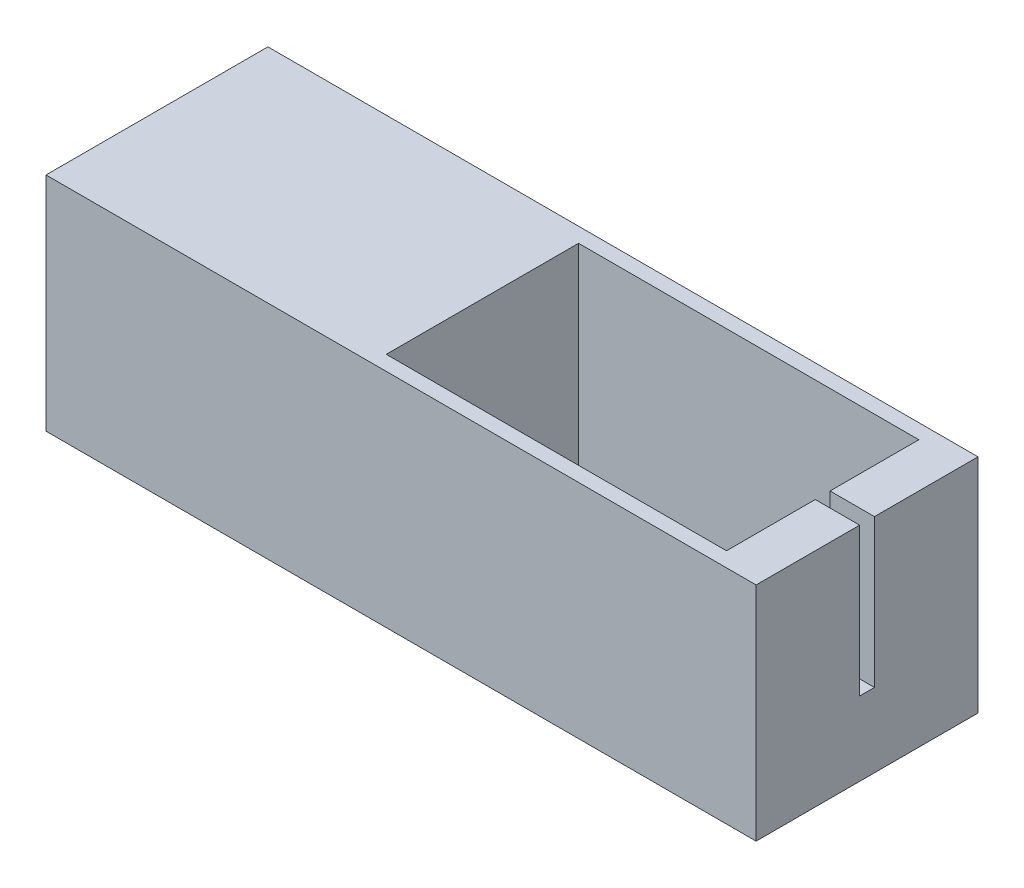
SolidWorks part; units mm, degrees
other "Markup1"
sketch "Sketch10" plane through (-5, 0, 7) normal (-0.8048, -0.3559, 0.4749) x (0.4785, -0.8625, 0.1645)
material "Very Low Density PE (SS)"
ref_plane "Front Plane" through (0, 0, 0) normal (0, 0, 1) x (1, 0, 0)
ref_plane "Top Plane" through (0, 0, 0) normal (0, 1, 0) x (1, 0, 0)
ref_plane "Right Plane" through (0, 0, 0) normal (1, 0, 0) x (0, 0, -1)
sketch "Sketch1" plane through (0, 0, 0) normal (0, 1, 0) x (1, 0, 0)
  circle A0 centre (0, 0) radius 3.5
  dimension "D1" = 7
extrude "Boss-Extrude1" add sketch "Sketch1" along normal blind 5
sketch "Sketch2" plane through (0, 0, 0) normal (0, -1, 0) x (1, 0, 0)
  circle A0 centre (0, 0) radius 2.5
  dimension "D1" = 5
extrude "Cut-Extrude1" cut sketch "Sketch2" against normal blind 4.5
sketch "Sketch3" plane through (0, 5, 0) normal (0, 1, 0) x (1, 0, 0)
  line L0 (0.3741, -3.4799) -> (14.7084, -1.9388)
  line L1 (14.7084, 1.9388) -> (0.3741, 3.4799)
  arc A0 (14.7084, -1.9388) -> (14.7084, 1.9388) centre (14.5, 0) ccw
  circle A1 centre (0, 0) radius 3.5 construction
  arc A2 (0.3741, -3.4799) -> (0.3741, 3.4799) centre (0, 0) ccw
  dimension "D1" = 14.5
  dimension "D2" = 1.95
extrude "Boss-Extrude2" add sketch "Sketch3" against normal blind 1
sketch "Sketch4" plane through (0, 5, 0) normal (0, 1, 0) x (1, 0, 0)
  line L1 (-4.5, 7.5) -> (17.5, 7.5)
  line L2 (0.3741, -3.4799) -> (14.7084, -1.9388)
  line L3 (14.7084, 1.9388) -> (0.3741, 3.4799)
  line L4 (0.3741, -3.4799) -> (14.7084, -1.9388)
  line L5 (14.7084, 1.9388) -> (0.3741, 3.4799)
  line L6 (-4.5, 7.5) -> (-4.5, -7.5)
  line L7 (-4.5, -7.5) -> (17.5, -7.5)
  line L8 (17.5, 7.5) -> (17.5, -7.5)
  arc A2 (0.3741, 3.4799) -> (0.3741, -3.4799) centre (0, 0) ccw
  arc A3 (14.7084, -1.9388) -> (14.7084, 1.9388) centre (14.5, 0) ccw
  arc A4 (0.3741, 3.4799) -> (0.3741, -3.4799) centre (0, 0) ccw
  arc A5 (14.7084, -1.9388) -> (14.7084, 1.9388) centre (14.5, 0) ccw
  dimension "D4" = 3
  dimension "D2" = 7.5
  dimension "D3" = 22
  dimension "D5" = 7.5
  dimension "D1" = 0
extrude "Boss-Extrude3" add sketch "Sketch4" against normal blind 5 separate body
sketch "Sketch5" plane through (0, 5, 0) normal (0, 1, 0) x (1, 0, 0)
  line L1 (-4.5, 7.5) -> (17.5, 7.5)
  line L2 (-4.5, 7.5) -> (-4.5, -7.5)
  line L3 (-4.5, -7.5) -> (17.5, -7.5)
  line L4 (17.5, 7.5) -> (17.5, -7.5)
extrude "Boss-Extrude4" add sketch "Sketch5" along normal blind 10
ref_plane "Plane1" through (6.5, 0, 0) normal (-1, 0, 0) x (0, 0, 1)
sketch "Sketch7" plane through (17.5, 0, 0) normal (1, 0, 0) x (0, 0, -1)
  line L1 (-7.5, 15) -> (7.5, 15)
  line L2 (-7.5, 15) -> (-7.5, 0)
  line L3 (-7.5, 0) -> (7.5, 0)
  line L4 (7.5, 15) -> (7.5, 0)
extrude "Boss-Extrude5" add sketch "Sketch7" along normal blind 26
sketch "Sketch8" plane through (0, 0, 0) normal (0, -1, 0) x (1, 0, 0)
  line L0 (43.5, 7.5) -> (43.5, -7.5) construction
  line L1 (17.5, 6.5) -> (40.5, 6.5)
  line L2 (17.5, 6.5) -> (17.5, -6.5)
  line L3 (17.5, -6.5) -> (40.5, -6.5)
  line L4 (40.5, 6.5) -> (40.5, -6.5)
  line L5 (43.5, -7.5) -> (-4.5, -7.5) construction
  dimension "D1" = 23
  dimension "D2" = 13
  dimension "D3" = 3
  dimension "D4" = 1
extrude "Cut-Extrude2" cut sketch "Sketch8" against normal blind 24
sketch "Sketch9" plane through (43.5, 0, 0) normal (1, 0, 0) x (0, 0, -1)
  line L0 (0, 15) -> (0, 5)
  line L1 (7.5, 15) -> (-7.5, 15) construction
  dimension "D1" = 10
extrude "Cut-Extrude-Thin1" cut sketch "Sketch9" against normal up to next (3 mm away) thin contours L0 thin type mid plane wall 1
